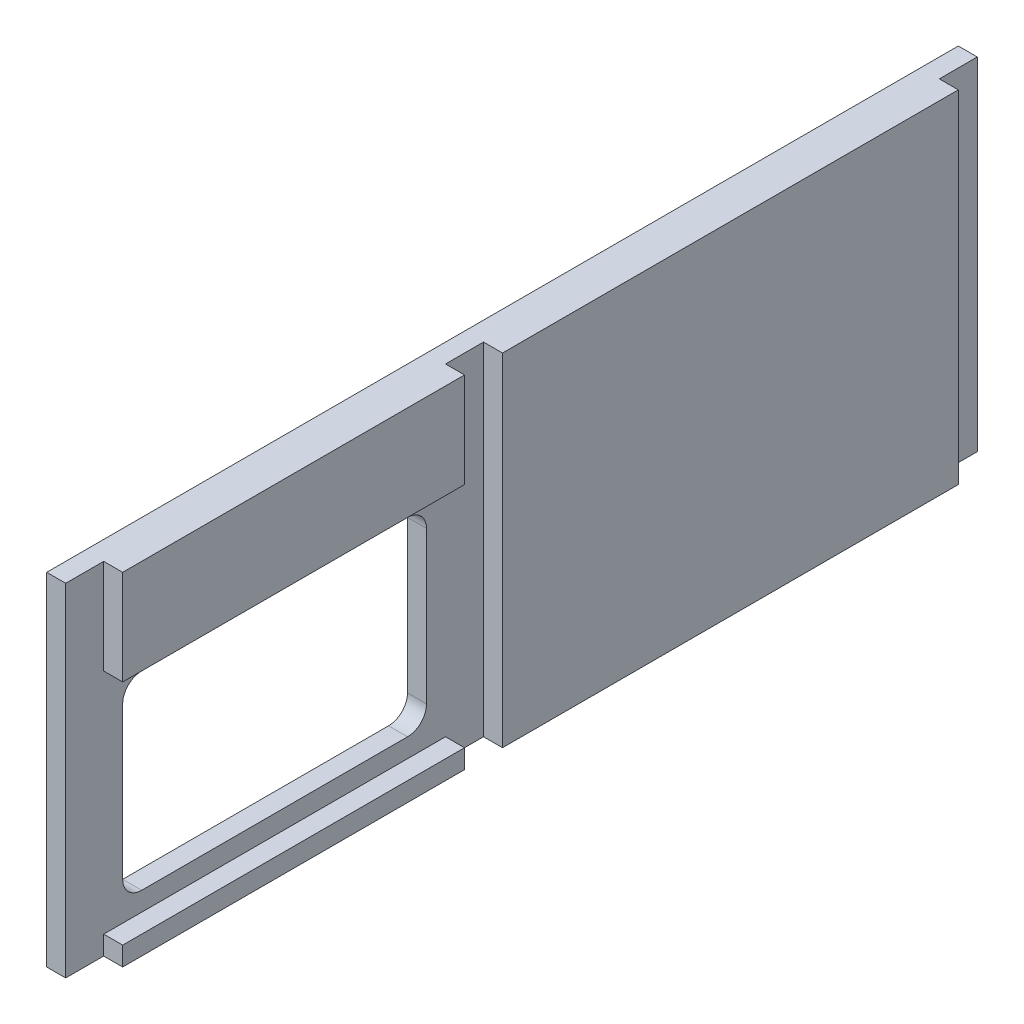
SolidWorks part; units mm, degrees
ref_plane "Front Plane" through (0, 0, 0) normal (0, 0, 1) x (1, 0, 0)
ref_plane "Top Plane" through (0, 0, 0) normal (0, 1, 0) x (1, 0, 0)
ref_plane "Right Plane" through (0, 0, 0) normal (1, 0, 0) x (0, 0, -1)
sketch "Sketch1" plane through (0, 0, 0) normal (1, 0, 0) x (0, 0, -1)
  line L1 (0, 0) -> (304.8, 0)
  line L2 (0, 0) -> (0, 114.3)
  line L3 (0, 114.3) -> (304.8, 114.3)
  line L4 (304.8, 0) -> (304.8, 114.3)
  dimension "D1" = 304.8
  dimension "D2" = 114.3
extrude "Boss-Extrude1" add sketch "Sketch1" along normal blind 12.7
sketch "Sketch2" plane through (12.7, 0, 0) normal (1, 0, 0) x (0, 0, -1)
  line L0 (0, 0) -> (304.8, 0) construction
  line L1 (0, 114.3) -> (12.7, 114.3)
  line L2 (0, 114.3) -> (0, 0)
  line L3 (0, 0) -> (12.7, 0)
  line L4 (12.7, 114.3) -> (12.7, 0)
  line L5 (304.8, 0) -> (304.8, 114.3) construction
  line L6 (304.8, 114.3) -> (292.1, 114.3)
  line L7 (304.8, 114.3) -> (304.8, 0)
  line L8 (304.8, 0) -> (292.1, 0)
  line L9 (292.1, 114.3) -> (292.1, 0)
  line L10 (304.8, 114.3) -> (0, 114.3) construction
  line L12 (127, 114.3) -> (139.7, 114.3)
  line L13 (127, 114.3) -> (127, 0)
  line L14 (127, 0) -> (139.7, 0)
  line L15 (139.7, 114.3) -> (139.7, 0)
  dimension "D1" = 12.7
  dimension "D2" = 12.7
  dimension "D3" = 12.7
  dimension "D4" = 152.4
extrude "Cut-Extrude1" cut sketch "Sketch2" against normal blind 6.35
sketch "Sketch3" plane through (12.7, 0, 0) normal (1, 0, 0) x (0, 0, -1)
  line L0 (12.7, 0) -> (127, 0) construction
  line L1 (12.7, 82.55) -> (127, 82.55)
  line L2 (12.7, 82.55) -> (12.7, 6.35)
  line L3 (12.7, 6.35) -> (127, 6.35)
  line L4 (127, 82.55) -> (127, 6.35)
  line L5 (12.7, 0) -> (12.7, 114.3) construction
  line L6 (127, 114.3) -> (127, 0) construction
  dimension "D1" = 6.35
  dimension "D2" = 76.2
extrude "Cut-Extrude2" cut sketch "Sketch3" against normal blind 6.35
sketch "Sketch4" plane through (6.35, 0, 0) normal (1, 0, 0) x (0, 0, -1)
  line L0 (19.05, 69.85) -> (19.05, 19.05)
  line L1 (12.7, 82.55) -> (127, 82.55) construction
  line L2 (12.7, 82.55) -> (12.7, 6.35) construction
  line L3 (12.7, 6.35) -> (127, 6.35) construction
  line L4 (127, 82.55) -> (127, 6.35) construction
  line L5 (25.4, 12.7) -> (114.3, 12.7)
  line L6 (120.65, 69.85) -> (120.65, 19.05)
  line L7 (25.4, 76.2) -> (114.3, 76.2)
  line L8 (19.05, 76.2) -> (19.05, 12.7) construction
  line L9 (19.05, 12.7) -> (120.65, 12.7) construction
  line L10 (120.65, 76.2) -> (120.65, 12.7) construction
  line L11 (19.05, 76.2) -> (120.65, 76.2) construction
  arc A0 (19.05, 19.05) -> (25.4, 12.7) centre (25.4, 19.05) ccw
  arc A1 (114.3, 12.7) -> (120.65, 19.05) centre (114.3, 19.05) ccw
  arc A2 (120.65, 69.85) -> (114.3, 76.2) centre (114.3, 69.85) ccw
  arc A3 (19.05, 69.85) -> (25.4, 76.2) centre (25.4, 69.85) cw
  dimension "D2" = 6.35
  dimension "D1" = 6.35
extrude "Cut-Extrude3" cut sketch "Sketch4" against normal through all
sketch "Sketch5" plane through (6.35, 0, 0) normal (1, 0, 0) x (0, 0, -1)
  line L0 (114.3, 76.2) -> (25.4, 76.2) construction
  line L1 (120.65, 19.05) -> (120.65, 69.85) construction
  line L2 (25.4, 12.7) -> (114.3, 12.7) construction
  line L3 (19.05, 69.85) -> (19.05, 19.05) construction
  line L4 (114.3, 76.2) -> (25.4, 76.2) construction
  line L5 (120.65, 19.05) -> (120.65, 69.85) construction
  line L6 (25.4, 12.7) -> (114.3, 12.7) construction
  line L7 (19.05, 69.85) -> (19.05, 19.05) construction
  line L8 (38.1, 63.5) -> (38.1, -8.9999) construction
  line L9 (12.7, 82.55) -> (127, 82.55)
  line L10 (12.7, 82.55) -> (12.7, 6.35)
  line L11 (12.7, 6.35) -> (127, 6.35)
  line L12 (127, 82.55) -> (127, 6.35)
  line L13 (31.75, 63.5) -> (44.45, 63.5)
  line L14 (31.75, 63.5) -> (31.75, 44.45)
  line L15 (31.75, 44.45) -> (44.45, 44.45)
  line L16 (44.45, 63.5) -> (44.45, 44.45)
  line L17 (44.45, 63.5) -> (31.75, 44.45)
  arc A0 (120.65, 69.85) -> (114.3, 76.2) centre (114.3, 69.85) ccw construction
  arc A1 (114.3, 12.7) -> (120.65, 19.05) centre (114.3, 19.05) ccw construction
  arc A2 (19.05, 19.05) -> (25.4, 12.7) centre (25.4, 19.05) ccw construction
  arc A3 (25.4, 76.2) -> (19.05, 69.85) centre (25.4, 69.85) ccw construction
  arc A4 (120.65, 69.85) -> (114.3, 76.2) centre (114.3, 69.85) ccw construction
  arc A5 (114.3, 12.7) -> (120.65, 19.05) centre (114.3, 19.05) ccw construction
  arc A6 (19.05, 19.05) -> (25.4, 12.7) centre (25.4, 19.05) ccw construction
  arc A7 (25.4, 76.2) -> (19.05, 69.85) centre (25.4, 69.85) ccw construction
  circle A8 centre (95.25, 30.48) radius 4.7625
  circle A9 centre (95.25, 58.42) radius 4.7625
  circle A10 centre (38.1, 25.4) radius 4.064
  circle A11 centre (95.25, 58.42) radius 12.7 construction
  circle A12 centre (95.25, 30.48) radius 12.7 construction
  circle A13 centre (95.25, 58.42) radius 0.2003
  circle A14 centre (95.25, 30.48) radius 0.2728
  circle A15 centre (38.1, 25.4) radius 0.202
  circle A16 centre (38.1, 53.975) radius 0.3999
  dimension "D1" = 9.525
  dimension "D2" = 9.525
  dimension "D3" = 8.128
  dimension "D9" = 25.4
  dimension "D10" = 25.4
  dimension "D4" = 12.7
  dimension "D5" = 19.05
  dimension "D6" = 12.7
  dimension "D7" = 12.7
  dimension "D8" = 12.7
  dimension "D11" = 17.78
  dimension "D12" = 17.78
  dimension "D13" = 25.4
  dimension "D14" = 25.4
